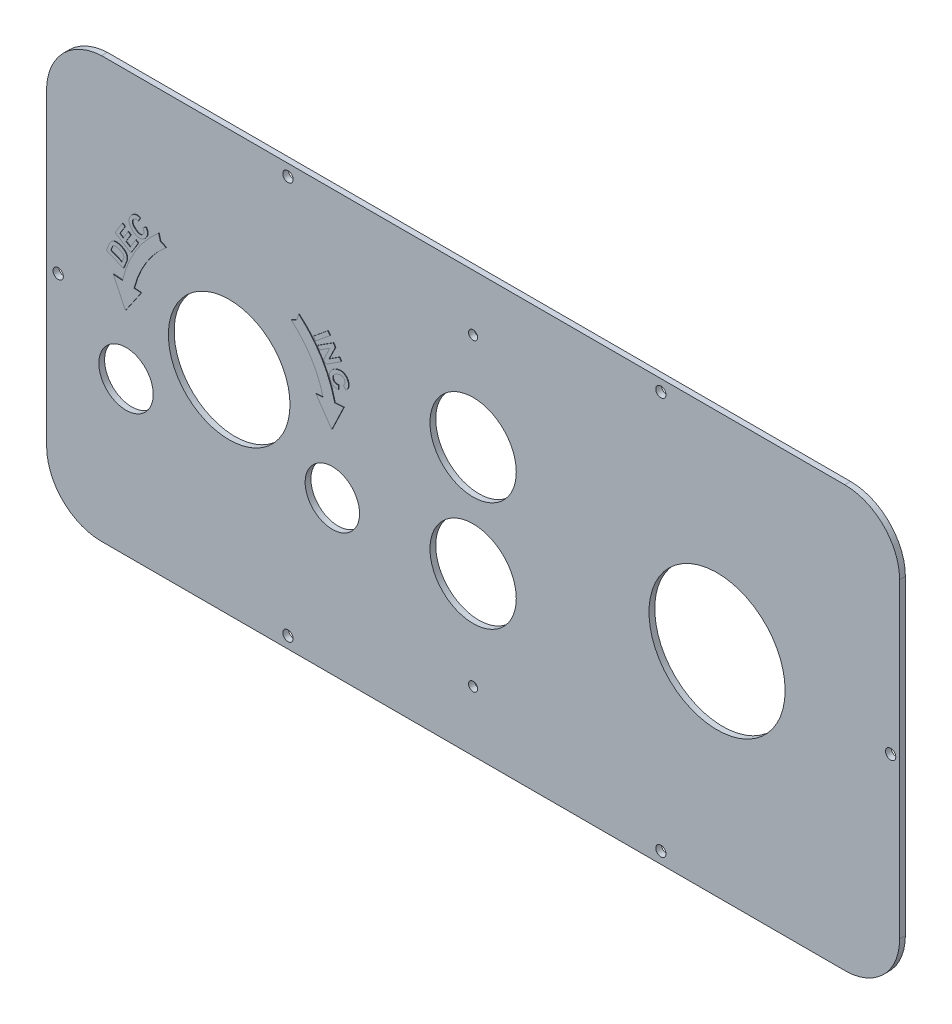
SolidWorks part; units mm, degrees
material "AISI 1020"
ref_plane "Front Plane" through (0, 0, 0) normal (0, 0, 1) x (1, 0, 0)
ref_plane "Top Plane" through (0, 0, 0) normal (0, 1, 0) x (1, 0, 0)
ref_plane "Right Plane" through (0, 0, 0) normal (1, 0, 0) x (0, 0, -1)
sketch "Sketch1" plane through (0, 0, 0) normal (0, 0, 1) x (1, 0, 0)
  line L0 (-332.2158, -23.1447) -> (-168.412, -23.1447)
  line L1 (-344.2939, -35.2228) -> (-344.2939, -103.7766)
  line L2 (-332.2158, -115.8547) -> (-167.8432, -115.8547)
  line L3 (-156.3339, -103.79) -> (-156.3339, -35.2228)
  line L4 (-250.3139, -35.5168) -> (-250.3139, -56.9362)
  line L5 (-250.3139, -56.9362) -> (-250.3139, -81.0662)
  line L6 (-250.3139, -81.0662) -> (-250.3139, -102.5895)
  line L7 (-250.3139, -23.1447) -> (-250.3139, -35.5168)
  arc A0 (-344.2939, -35.2228) -> (-332.2158, -23.1447) centre (-331.6084, -35.8302) cw
  arc A1 (-344.2939, -103.7766) -> (-332.2158, -115.8547) centre (-332.2158, -103.7766) ccw
  arc A2 (-168.412, -23.1447) -> (-156.3339, -35.2228) centre (-168.412, -35.2228) cw
  arc A3 (-167.8432, -115.8547) -> (-156.3339, -103.79) centre (-168.412, -103.79) ccw
  circle A14 centre (-291.1227, -113.312) radius 1.1315
  circle A15 centre (-208.9363, -113.312) radius 1.1315
  circle A16 centre (-158.3079, -69.4997) radius 1.1315
  circle A17 centre (-208.9363, -25.6875) radius 1.1315
  circle A18 centre (-291.1227, -25.6875) radius 1.143
  circle A19 centre (-341.7511, -69.4997) radius 1.1315
  circle A20 centre (-250.3139, -81.0662) radius 9.5103
  circle A21 centre (-250.3139, -56.9362) radius 9.5103
  circle A22 centre (-250.3139, -35.5168) radius 1.0011
  circle A23 centre (-250.3139, -102.5895) radius 1.0011
  dimension "D3" = 12.7
  dimension "D5" = 2.286
  dimension "D1" = 92.71
  dimension "D2" = 187.96
  dimension "D4" = 24.13
extrude "Boss-Extrude1" add sketch "Sketch1" along normal blind 1.27
sketch "Sketch2" plane through (0, 0, 1.27) normal (0, 0, 1) x (1, 0, 0)
  line L0 (-250.3139, -56.9362) -> (-250.3139, -81.0662) construction
  line L1 (-250.3139, -69.0012) -> (-196.5594, -69.0012) construction
  line L2 (-250.3139, -69.0012) -> (-304.0684, -69.0012) construction
  line L3 (-304.0684, -69.0012) -> (-326.8005, -82.1256) construction
  line L4 (-304.0684, -69.0012) -> (-281.3363, -82.1256) construction
  circle A0 centre (-196.5594, -69.0012) radius 14.9987
  circle A1 centre (-304.0684, -69.0012) radius 13.3985
  circle A2 centre (-326.8005, -82.1256) radius 5.9944
  circle A3 centre (-281.3363, -82.1256) radius 5.9944
  dimension "D1" = 11.9888
  dimension "D2" = 11.9888
  dimension "D3" = 26.797
  dimension "D4" = 29.9974
  dimension "D5" = 120
  dimension "D6" = 30
extrude "Cut-Extrude1" cut sketch "Sketch2" against normal blind 3.81
sketch "Sketch3" plane through (0, 0, 1.27) normal (0, 0, 1) x (1, 0, 0)
  line L0 (-304.0684, -69.0012) -> (-326.8005, -69.0012)
  line L1 (-304.0684, -69.0012) -> (-318.6803, -51.5874)
  line L2 (-326.8005, -82.1256) -> (-326.8005, -69.0012)
  line L3 (-318.6803, -51.5874) -> (-319.4966, -50.6145)
  line L4 (-326.8005, -69.0012) -> (-323.3227, -63.9362)
  line L5 (-323.3227, -63.9362) -> (-329.448, -63.4569)
  line L6 (-329.448, -63.4569) -> (-326.8005, -69.0012)
  line L7 (-319.4966, -50.6145) -> (-319.12, -51.966)
  line L8 (-319.12, -51.966) -> (-317.8639, -52.5603)
  line L9 (-304.0684, -69.0012) -> (-304.0684, -32.3623) construction
  line L10 (-289.0168, -51.966) -> (-290.2728, -52.5603)
  line L11 (-288.6401, -50.6145) -> (-289.0168, -51.966)
  line L12 (-278.6888, -63.4569) -> (-281.3363, -69.0012)
  line L13 (-284.814, -63.9362) -> (-278.6888, -63.4569)
  line L14 (-281.3363, -69.0012) -> (-284.814, -63.9362)
  line L15 (-289.4565, -51.5874) -> (-288.6401, -50.6145)
  line L16 (-290.2728, -52.5603) -> (-289.4565, -51.5874)
  circle A0 centre (-304.0684, -69.0012) radius 22.7321
  circle A1 centre (-326.5237, -65.4648) radius 1.7736 construction
  circle A2 centre (-304.0684, -69.0012) radius 24.0021
  circle A3 centre (-304.0684, -69.0012) radius 21.4621
  circle A4 centre (-281.613, -65.4648) radius 1.7736 construction
  dimension "D2" = 1.27
  dimension "D3" = 1.27
  dimension "D1" = 50
extrude "Boss-Extrude2" add sketch "Sketch3" along normal blind 0.127 contours A2 L5 L6 | L5 A2 L6 A0 | A3 L5 A0 L4 | L5 A3 L4 | A3 L8 A0 L5 | L7 A2 L5 A0 | L14 A3 L13 | A3 L14 A0 L13 | L12 A2 L13 A0 | A2 L12 L13 | L13 A2 L11 A0 | A3 L13 A0 L10
sketch "Sketch4" plane through (0, 0, 1.27) normal (0, 0, 1) x (1, 0, 0)
  arc A0 (-321.1442, -51.4577) -> (-328.5501, -68.9783) centre (-304.0684, -69.0012) ccw construction
  text T0 "DEC" font "Arial" height in points 16
extrude "Boss-Extrude3" add sketch "Sketch4" along normal blind 0.127
sketch "Sketch5" plane through (0, 0, 1.27) normal (0, 0, 1) x (1, 0, 0)
  arc A0 (-280.8362, -61.3799) -> (-286.8256, -51.6661) centre (-304.0684, -69.0012) ccw construction
  text T0 "INC" font "Arial" height in points 16
extrude "Boss-Extrude4" add sketch "Sketch5" along normal blind 0.127
